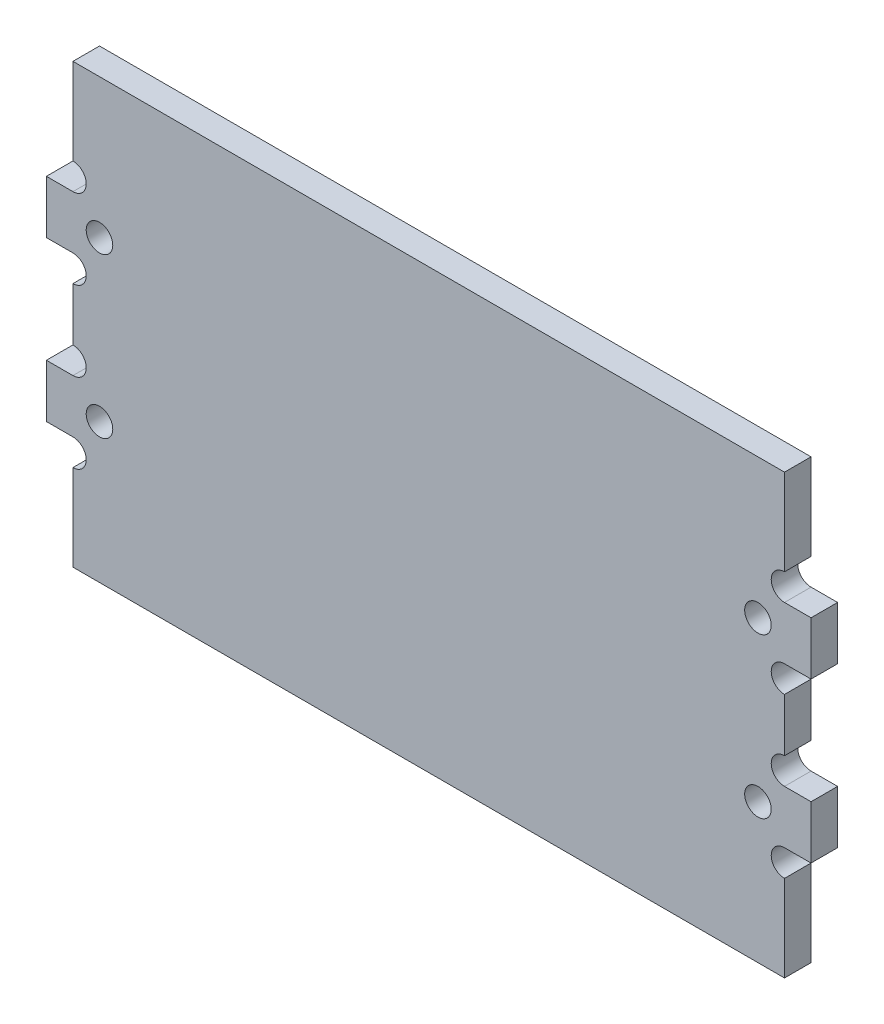
SolidWorks part; units mm, degrees
material "自訂玻璃纖維"
ref_plane "前基準面" through (0, 0, 0) normal (0, 0, 1) x (1, 0, 0)
ref_plane "上基準面" through (0, 0, 0) normal (0, 1, 0) x (1, 0, 0)
ref_plane "右基準面" through (0, 0, 0) normal (1, 0, 0) x (0, 0, -1)
sketch "草圖1" plane through (0, 0, 0) normal (0, 0, 1) x (1, 0, 0)
  line L0 (-28.1616, 19.348) -> (-29.1616, 19.348)
  line L1 (-28.1616, 19.348) -> (23.4384, 19.348)
  line L2 (-29.1616, 18.348) -> (-29.1616, 12.848)
  line L3 (-28.1616, -13.652) -> (23.4384, -13.652)
  line L4 (24.4384, 18.348) -> (24.4384, 12.848)
  line L5 (-29.1616, 19.348) -> (-29.1616, 18.348)
  line L6 (23.4384, 19.348) -> (24.4384, 19.348)
  line L7 (24.4384, 19.348) -> (24.4384, 18.348)
  line L8 (24.4384, -12.652) -> (24.4384, -13.652)
  line L9 (24.4384, -13.652) -> (23.4384, -13.652)
  line L10 (-29.1616, -12.652) -> (-29.1616, -13.652)
  line L11 (-29.1616, -13.652) -> (-28.1616, -13.652)
  line L12 (-29.1616, 4.848) -> (-29.1616, 0.848)
  line L13 (-29.1616, 10.848) -> (-31.1616, 10.848)
  line L14 (-29.1616, -5.152) -> (-31.1616, -5.152)
  line L15 (-29.1616, 6.848) -> (-31.1616, 6.848)
  line L16 (-31.1616, 10.848) -> (-31.1616, 6.848)
  line L17 (-31.1616, -1.152) -> (-31.1616, -5.152)
  line L18 (-29.1616, -1.152) -> (-31.1616, -1.152)
  line L19 (-29.1616, -7.152) -> (-29.1616, -12.652)
  line L20 (24.4384, -7.152) -> (24.4384, -12.652)
  line L21 (24.4384, -1.152) -> (26.4384, -1.152)
  line L22 (26.4384, -1.152) -> (26.4384, -5.152)
  line L23 (26.4384, 10.848) -> (26.4384, 6.848)
  line L24 (24.4384, 6.848) -> (26.4384, 6.848)
  line L25 (24.4384, -5.152) -> (26.4384, -5.152)
  line L26 (24.4384, 10.848) -> (26.4384, 10.848)
  line L27 (24.4384, 4.848) -> (24.4384, 0.848)
  circle A0 centre (22.4384, 8.848) radius 1
  arc A1 (-29.1616, 10.848) -> (-29.1616, 12.848) centre (-29.1616, 11.848) ccw
  circle A2 centre (-27.1616, 8.848) radius 1
  circle A3 centre (-27.1616, -3.152) radius 1
  circle A4 centre (22.4384, -3.152) radius 1
  arc A5 (-29.1616, 6.848) -> (-29.1616, 4.848) centre (-29.1616, 5.848) cw
  arc A6 (-29.1616, -1.152) -> (-29.1616, 0.848) centre (-29.1616, -0.152) ccw
  arc A7 (-29.1616, -5.152) -> (-29.1616, -7.152) centre (-29.1616, -6.152) cw
  arc A8 (24.4384, -5.152) -> (24.4384, -7.152) centre (24.4384, -6.152) ccw
  arc A9 (24.4384, -1.152) -> (24.4384, 0.848) centre (24.4384, -0.152) cw
  arc A10 (24.4384, 6.848) -> (24.4384, 4.848) centre (24.4384, 5.848) ccw
  arc A11 (24.4384, 10.848) -> (24.4384, 12.848) centre (24.4384, 11.848) cw
  point P10 (-29.1616, -13.652)
  point P15 (24.4384, 19.348)
  point P18 (-29.1616, 19.348)
  dimension "D3" = 2
  dimension "D4" = 4
  dimension "D5" = 2
  dimension "D6" = 12
  dimension "D7" = 2
  dimension "D9" = 2
  dimension "D1" = 53.6
  dimension "D2" = 33
extrude "填料-伸長1" add sketch "草圖1" along normal blind 2
